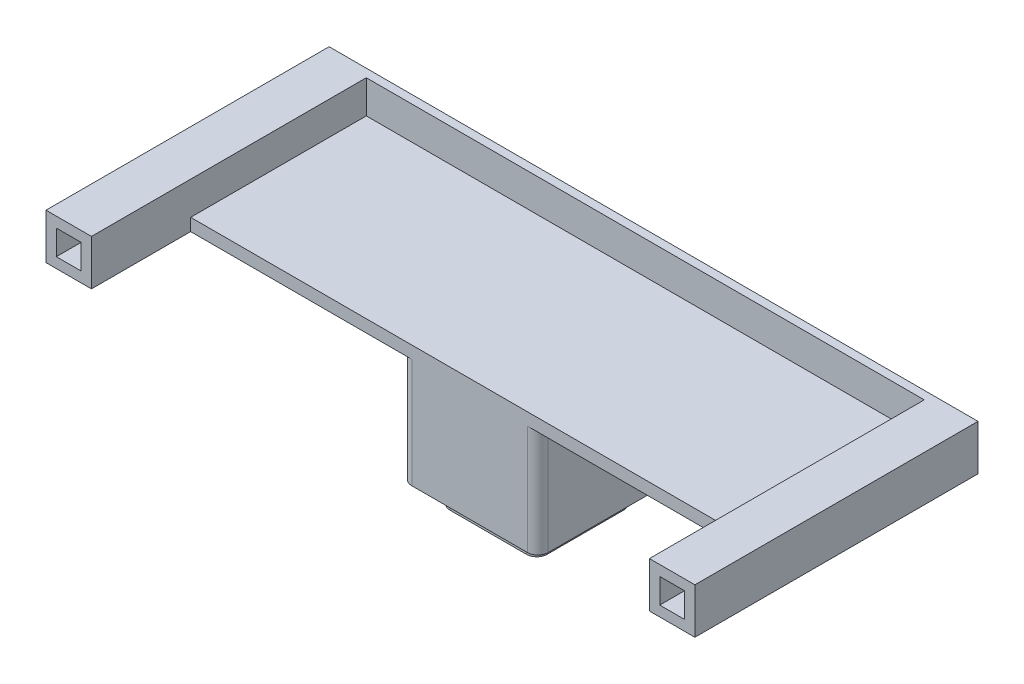
SolidWorks part; units mm, degrees
ref_plane "Plan de face" through (0, 0, 0) normal (0, 0, 1) x (1, 0, 0)
ref_plane "Plan de dessus" through (0, 0, 0) normal (0, 1, 0) x (1, 0, 0)
ref_plane "Plan de droite" through (0, 0, 0) normal (1, 0, 0) x (0, 0, -1)
sketch "Esquisse1" plane through (0, 0, 0) normal (0, 1, 0) x (1, 0, 0)
  line L1 (0, 0) -> (314, 0)
  line L2 (0, 0) -> (0, 137)
  line L3 (0, 137) -> (314, 137)
  line L4 (314, 0) -> (314, 137)
  dimension "D1" = 137
  dimension "D2" = 314
extrude "Boss.-Extru.1" add sketch "Esquisse1" along normal blind 85
sketch "Esquisse2" plane through (0, 0, 0) normal (0, -1, 0) x (1, 0, 0)
  line L0 (314, -137) -> (0, -137) construction
  line L1 (0, 0) -> (124, 0)
  line L2 (0, 0) -> (0, -137)
  line L3 (0, -137) -> (124, -137)
  line L4 (124, 0) -> (124, -137)
  dimension "D1" = 124
extrude "Enlèv. mat.-Extru.1" cut sketch "Esquisse2" against normal blind 63
sketch "Esquisse3" plane through (0, 0, 0) normal (0, -1, 0) x (-1, 0, 0)
  line L0 (-314, 137) -> (-124, 137) construction
  line L1 (-314, 0) -> (-190, 0)
  line L2 (-314, 0) -> (-314, 137)
  line L3 (-314, 137) -> (-190, 137)
  line L4 (-190, 0) -> (-190, 137)
  dimension "D1" = 124
extrude "Enlèv. mat.-Extru.2" cut sketch "Esquisse3" against normal blind 63
sketch "Esquisse4" plane through (0, 0, 0) normal (0, -1, 0) x (1, 0, 0)
  line L0 (190, 0) -> (190, -137) construction
  line L1 (124, -137) -> (190, -137)
  line L2 (124, -137) -> (124, -112)
  line L3 (124, -112) -> (190, -112)
  line L4 (190, -137) -> (190, -112)
  dimension "D1" = 25
extrude "Enlèv. mat.-Extru.3" cut sketch "Esquisse4" against normal blind 63
sketch "Esquisse7" plane through (0, 85, 0) normal (0, 1, 0) x (1, 0, 0)
  line L0 (0, 0) -> (314, 0) construction
  line L1 (22, 0) -> (292, 0)
  line L2 (22, 0) -> (22, 133)
  line L3 (22, 133) -> (292, 133)
  line L4 (292, 0) -> (292, 133)
  line L5 (314, 137) -> (0, 137) construction
  line L10 (0, 137) -> (0, 0) construction
  line L11 (157, 137) -> (157, 0) construction
  line L12 (314, 0) -> (314, 137) construction
  dimension "D1" = 4
  dimension "D2" = 22
  dimension "D3" = 22
extrude "Enlèv. mat.-Extru.6" cut sketch "Esquisse7" against normal blind 16
sketch "Esquisse8" plane through (0, 0, 0) normal (0, 0, 1) x (1, 0, 0)
  line L0 (0, 85) -> (22, 85) construction
  line L1 (5, 80) -> (17, 80)
  line L2 (5, 80) -> (5, 68)
  line L3 (5, 68) -> (17, 68)
  line L4 (17, 80) -> (17, 68)
  line L5 (0, 85) -> (0, 63) construction
  line L6 (124, 63) -> (0, 63) construction
  line L7 (22, 69) -> (22, 85) construction
  line L8 (157, 69) -> (157, 2.1612) construction
  line L15 (22, 69) -> (292, 69) construction
  line L16 (297, 80) -> (297, 68)
  line L17 (309, 68) -> (297, 68)
  line L18 (309, 80) -> (309, 68)
  line L19 (309, 80) -> (297, 80)
  dimension "D1" = 5
  dimension "D2" = 5
  dimension "D3" = 5
  dimension "D4" = 5
extrude "Enlèv. mat.-Extru.7" cut sketch "Esquisse8" against normal blind 140
sketch "Esquisse9" plane through (0, 85, 0) normal (0, 1, 0) x (1, 0, 0)
  line L0 (292, 0) -> (292, 133) construction
  line L1 (22, 0) -> (292, 0)
  line L2 (22, 0) -> (22, 48)
  line L3 (22, 48) -> (292, 48)
  line L4 (292, 0) -> (292, 48)
  line L5 (314, 137) -> (0, 137) construction
  dimension "D1" = 89
extrude "Enlèv. mat.-Extru.8" cut sketch "Esquisse9" against normal blind 140
sketch "Esquisse5" plane through (0, 0, 0) normal (0, -1, 0) x (1, 0, 0)
  line L1 (139.5, -63) -> (174.5, -63)
  line L2 (139.5, -63) -> (139.5, -98)
  line L3 (139.5, -98) -> (174.5, -98)
  line L4 (174.5, -63) -> (174.5, -98)
  line L7 (157, -48) -> (157, -125.8431) construction
  line L8 (124, -48) -> (190, -48) construction
  point P10 (139.5, -80.5)
  dimension "D1" = 15
  dimension "D2" = 17.5
  dimension "D3" = 17.5
  dimension "D4" = 35
extrude "Enlèv. mat.-Extru.4" cut sketch "Esquisse5" against normal blind 38
sketch "Esquisse6" plane through (0, 0, 0) normal (0, -1, 0) x (-1, 0, 0)
  line L0 (-139.5, 63) -> (-139.5, 98) construction
  line L1 (-133.5, 57) -> (-180.5, 57)
  line L2 (-133.5, 57) -> (-133.5, 104)
  line L3 (-133.5, 104) -> (-180.5, 104)
  line L4 (-180.5, 57) -> (-180.5, 104)
  line L5 (-174.5, 98) -> (-174.5, 63) construction
  line L6 (-174.5, 63) -> (-139.5, 63) construction
  line L7 (-139.5, 98) -> (-174.5, 98) construction
  line L16 (-190, 48) -> (-190, 112) construction
  line L17 (-314, 137) -> (-314, 0) construction
  dimension "D1" = 6
  dimension "D2" = 6
  dimension "D3" = 6
  dimension "D4" = 6
  dimension "D5" = 124
extrude "Enlèv. mat.-Extru.5" cut sketch "Esquisse6" against normal blind 10
fillet "Congé1" radius 5 4 edges at (180.5, 5, -104) (133.5, 5, -104) (180.5, 5, -57) (133.5, 5, -57)
fillet "Congé2" radius 5 4 edges at (190, 36.5, -112) (124, 36.5, -112) (124, 36.5, -48) (190, 36.5, -48)
ref_plane "Plan1" through (22, 85, -133) normal (-1, 0, 0) x (0, 0, 1)
